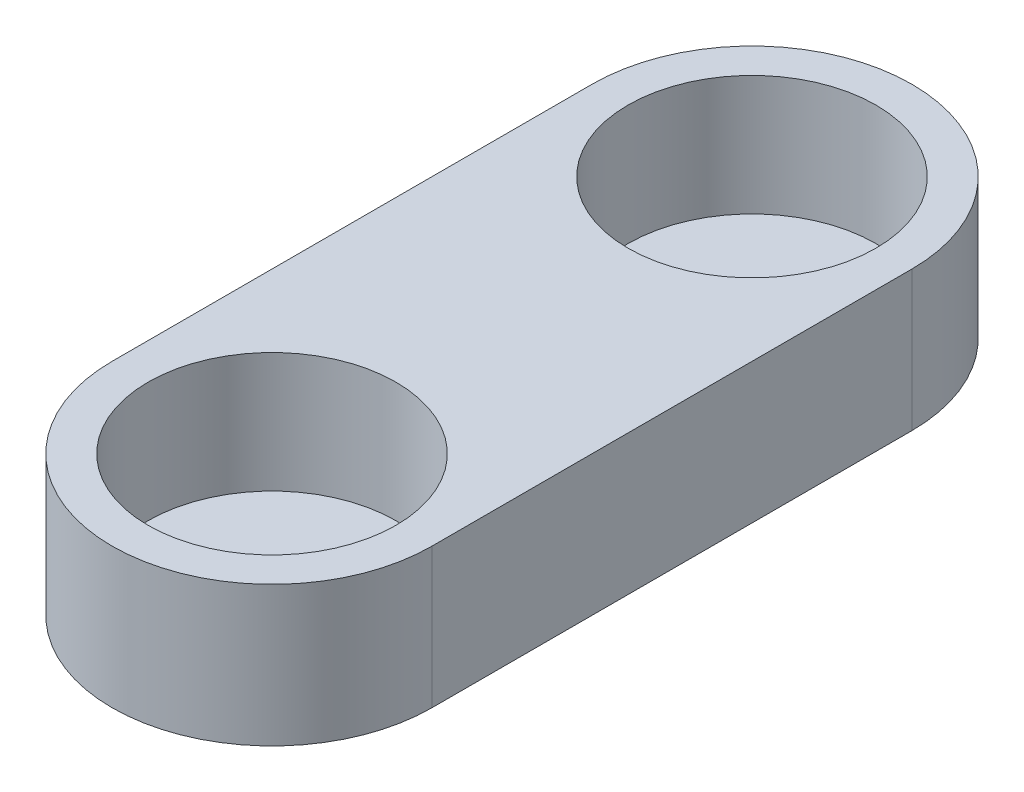
SolidWorks part; units mm, degrees
ref_plane "Front Plane" through (0, 0, 0) normal (0, 0, 1) x (1, 0, 0)
ref_plane "Top Plane" through (0, 0, 0) normal (0, 1, 0) x (1, 0, 0)
ref_plane "Right Plane" through (0, 0, 0) normal (1, 0, 0) x (0, 0, -1)
sketch "Sketch1" plane through (0, 0, 0) normal (0, 1, 0) x (1, 0, 0)
  line L0 (0, 6) -> (0, -6) construction
  line L1 (4, 6) -> (4, -6)
  line L2 (-4, 6) -> (-4, -6)
  arc A1 (4, 6) -> (-4, 6) centre (0, 6) ccw
  arc A2 (-4, -6) -> (4, -6) centre (0, -6) ccw
  circle A3 centre (0, 6) radius 3.1
  circle A4 centre (0, -6) radius 3.1
  point P5 (0, 0)
  dimension "D2" = 6.2
  dimension "D3" = 4
  dimension "D4" = 12
extrude "Boss-Extrude1" add sketch "Sketch1" along normal blind 3
sketch "Sketch2" plane through (0, 0, 0) normal (0, -1, 0) x (1, 0, 0)
  line L0 (0, 6) -> (0, -6) construction
  line L1 (4, 6) -> (4, -6)
  line L2 (-4, 6) -> (-4, -6)
  arc A0 (4, 6) -> (-4, 6) centre (0, 6) ccw
  arc A1 (-4, -6) -> (4, -6) centre (0, -6) ccw
  point P4 (0, 0)
extrude "Boss-Extrude2" add sketch "Sketch2" along normal blind 0.5
sketch "Sketch3" plane through (0, -0.5, 0) normal (0, -1, 0) x (1, 0, 0)
  circle A0 centre (0, 0) radius 0.85
  dimension "D1" = 1.7
extrude "Cut-Extrude1" cut sketch "Sketch3" against normal blind 2.5
sketch "Sketch4" plane through (0, -0.5, 0) normal (0, -1, 0) x (1, 0, 0)
  circle A0 centre (0, 6) radius 1
  circle A1 centre (0, -6) radius 1
  dimension "D1" = 2
extrude "Cut-Extrude2" cut sketch "Sketch4" against normal through all
